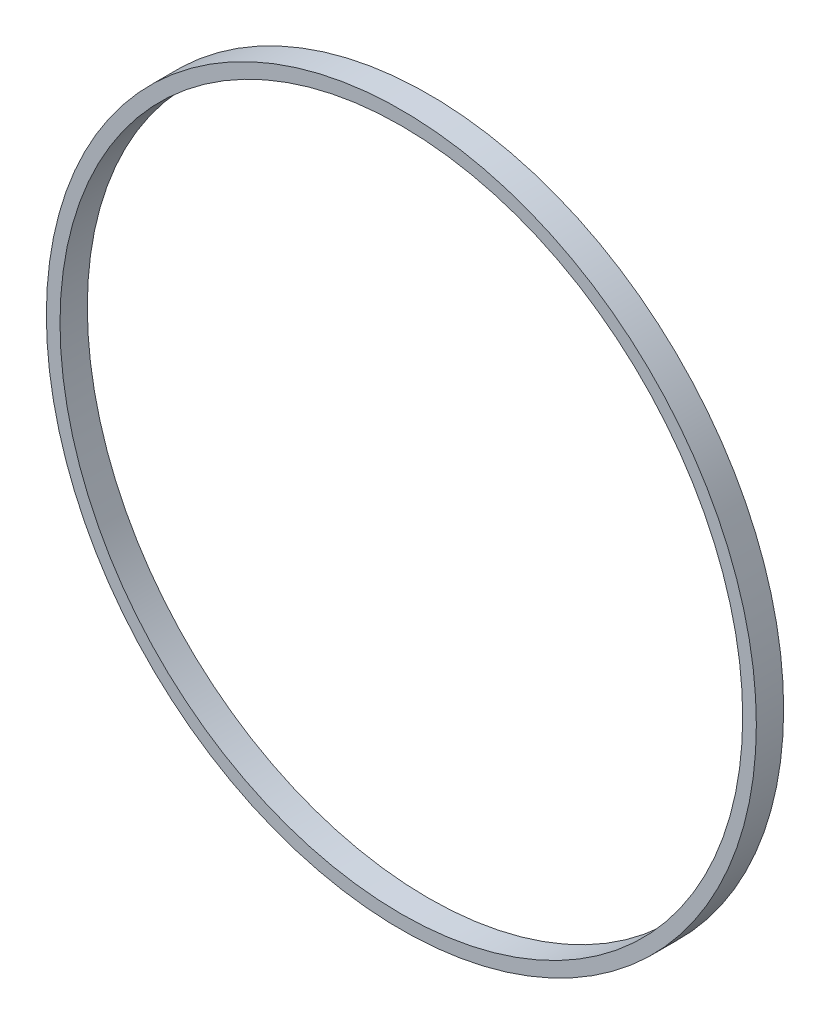
SolidWorks part; units mm, degrees
ref_plane "Front Plane" through (0, 0, 0) normal (0, 0, 1) x (1, 0, 0)
ref_plane "Top Plane" through (0, 0, 0) normal (0, 1, 0) x (1, 0, 0)
ref_plane "Right Plane" through (0, 0, 0) normal (1, 0, 0) x (0, 0, -1)
sketch "Sketch1" plane through (0, 0, 0) normal (0, 0, 1) x (1, 0, 0)
  line L0 (78.4818, 151.5744) -> (392.4092, 151.5744) construction
  circle A0 centre (0, 0) radius 66.04
  circle A1 centre (0, 0) radius 63.5
  dimension "D1" = 132.08
  dimension "D2" = 127
extrude "Boss-Extrude1" add sketch "Sketch1" along normal blind 5.08
